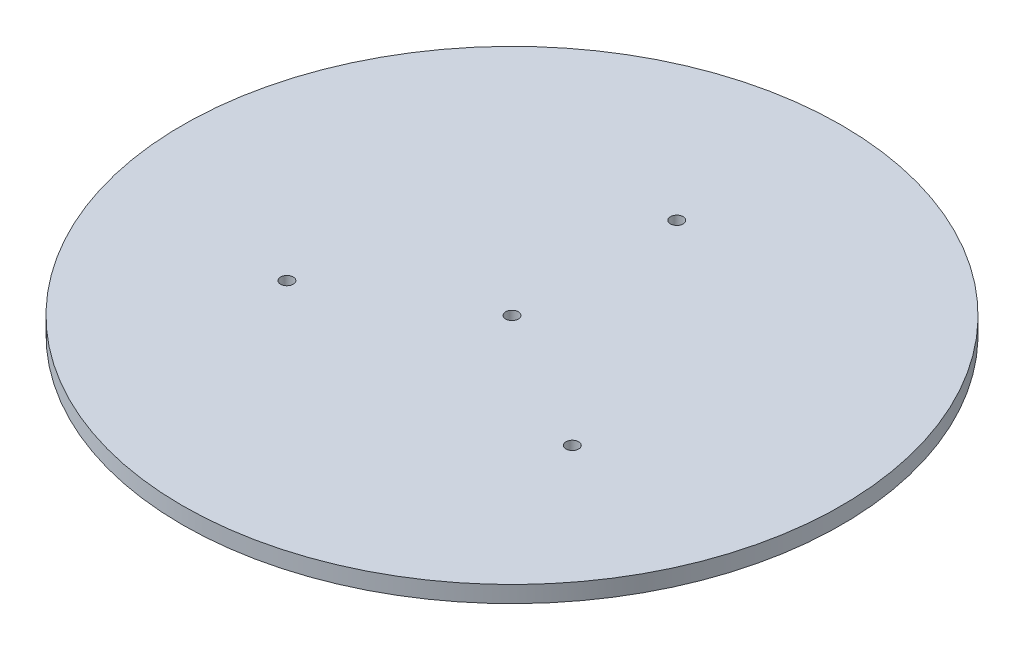
SolidWorks part; units mm, degrees
ref_plane "Front Plane" through (0, 0, 0) normal (0, 0, 1) x (1, 0, 0)
ref_plane "Top Plane" through (0, 0, 0) normal (0, 1, 0) x (1, 0, 0)
ref_plane "Right Plane" through (0, 0, 0) normal (1, 0, 0) x (0, 0, -1)
sketch "Sketch1" plane through (0, 0, 0) normal (0, 1, 0) x (1, 0, 0)
  line L0 (0, 0) -> (0, 126.1427) construction
  circle A0 centre (0, 0) radius 126.1427
  circle A1 centre (0, 63.0714) radius 2.4257
  circle A2 centre (54.6214, -31.5357) radius 2.4257
  circle A3 centre (-54.6214, -31.5357) radius 2.4257
  circle A4 centre (0, 0) radius 2.4257
  point P13 (0, 0)
  dimension "D1" = 252.2855
  dimension "D2" = 4.8514
  dimension "D4" = 4.8514
  dimension "D3" = 3
extrude "Boss-Extrude1" add sketch "Sketch1" along normal blind 6.35
